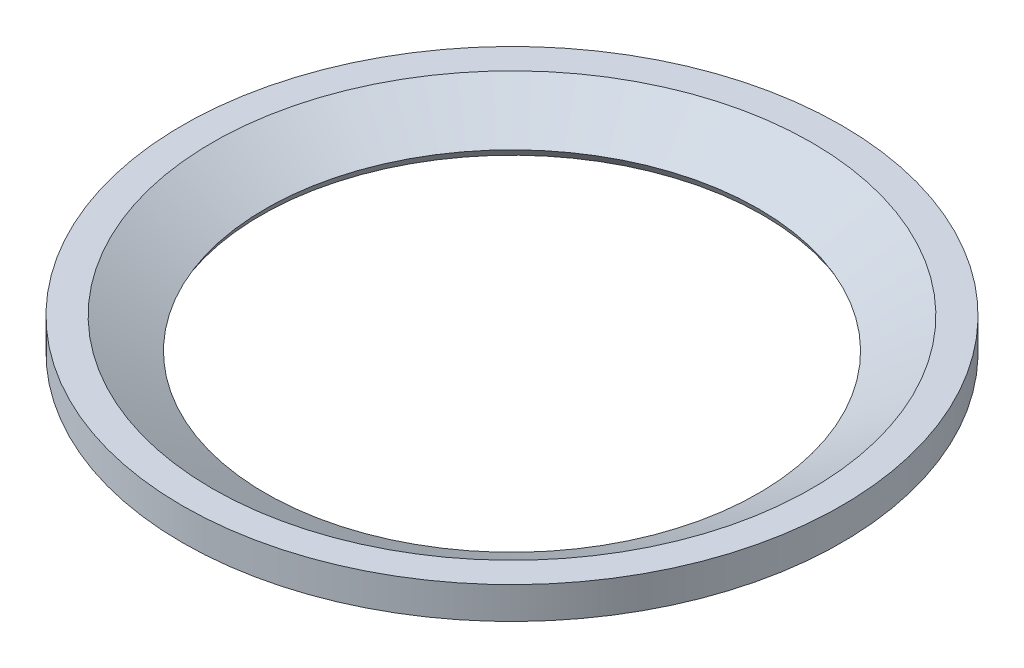
SolidWorks part; units mm, degrees
ref_plane "Front Plane" through (0, 0, 0) normal (0, 0, 1) x (1, 0, 0)
ref_plane "Top Plane" through (0, 0, 0) normal (0, 1, 0) x (1, 0, 0)
ref_plane "Right Plane" through (0, 0, 0) normal (1, 0, 0) x (0, 0, -1)
sketch "Sketch1" plane through (0, 0, 0) normal (0, 0, 1) x (1, 0, 0)
  line L0 (-44.577, 0) -> (-34.925, 5.5726) construction
  line L1 (-44.577, 0) -> (44.577, 0) construction
  line L2 (0, 0) -> (0, 5.5726) construction
  line L3 (-34.925, 5.5726) -> (34.925, 5.5726) construction
  line L4 (-44.577, 0) -> (-44.577, -3.175)
  line L5 (-44.577, 0) -> (-42.037, 0)
  line L6 (-42.037, 0) -> (-34.925, -4.1061)
  dimension "D1" = 89.154
  dimension "D2" = 30
  dimension "D3" = 69.85
  dimension "D4" = 3.175
  dimension "D5" = 2.54
  dimension "D6" = 30
revolve "Revolve-Thin1" add sketch "Sketch1" angle 360 about L2
